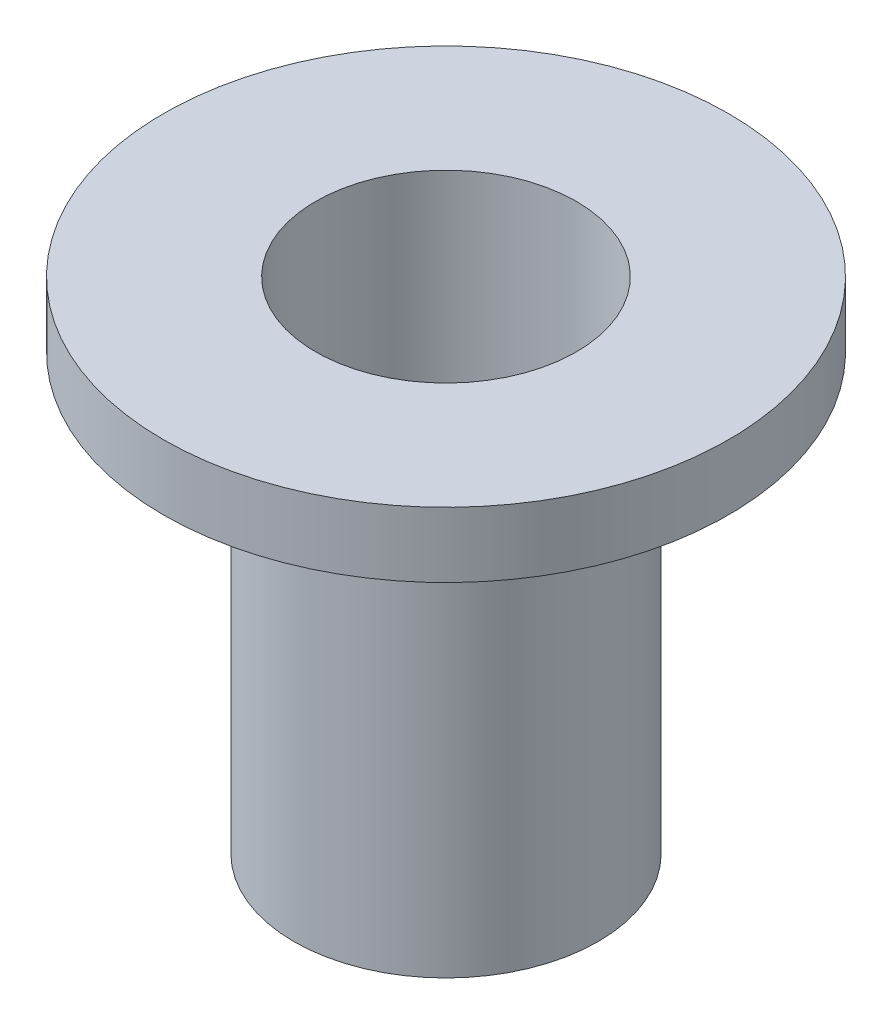
SolidWorks part; units mm, degrees
ref_plane "Front Plane" through (0, 0, 0) normal (0, 0, 1) x (1, 0, 0)
ref_plane "Top Plane" through (0, 0, 0) normal (0, 1, 0) x (1, 0, 0)
ref_plane "Right Plane" through (0, 0, 0) normal (1, 0, 0) x (0, 0, -1)
sketch "Sketch2" plane through (0, 0, 0) normal (0, 0, 1) x (1, 0, 0)
  line L0 (6, 16.8462) -> (6, -3.1538)
  line L1 (7, 16.8462) -> (7, -3.1538)
  line L2 (7, 16.8462) -> (13, 16.8462)
  line L3 (13, 16.8462) -> (13, 19.8462)
  line L4 (13, 19.8462) -> (6, 19.8462)
  line L5 (6, 19.8462) -> (6, 16.8462)
  line L7 (0, 0) -> (0, 32.007) construction
  line L8 (6, -3.1538) -> (7, -3.1538)
  dimension "D1" = 6
  dimension "D3" = 3
  dimension "D4" = 6
  dimension "D5" = 20
  dimension "D6" = 19.8462
  dimension "D2" = 1
revolve "Revolve1" add sketch "Sketch2" angle 360 about L7
